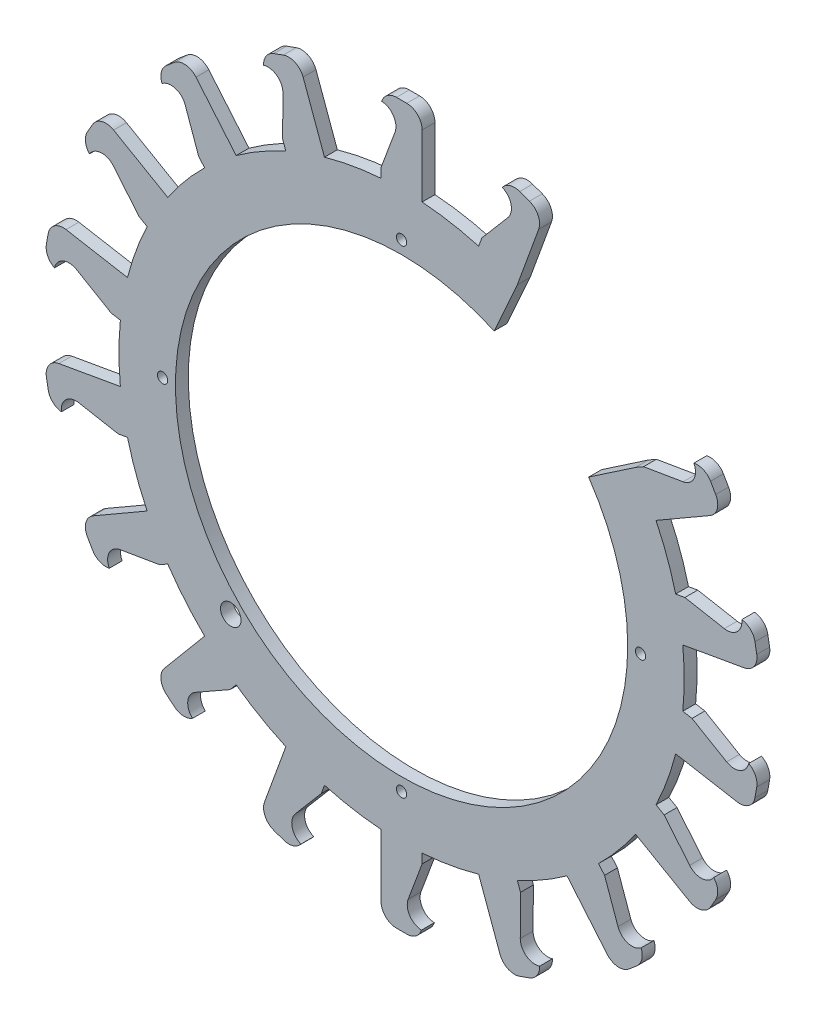
SolidWorks part; units mm, degrees
ref_plane "Front Plane" through (0, 0, 0) normal (0, 0, 1) x (1, 0, 0)
ref_plane "Top Plane" through (0, 0, 0) normal (0, 1, 0) x (1, 0, 0)
ref_plane "Right Plane" through (0, 0, 0) normal (1, 0, 0) x (0, 0, -1)
sketch "Sketch1" plane through (0, 0, 0) normal (0, 0, 1) x (1, 0, 0)
  line L0 (-78.3987, -3.3654) -> (61.3013, -3.3654) construction
  line L1 (-5.8227, 60.5836) -> (-5.8227, 59.1774)
  line L2 (-57.9401, 46.026) -> (40.8427, -52.7569) construction
  line L3 (40.8427, 46.026) -> (-57.9401, -52.7569) construction
  line L4 (-13.4427, 60.5073) -> (-13.4427, 59.1774)
  line L5 (-13.4427, 59.1774) -> (-5.8227, 59.1774)
  line L12 (2.7798, 58.212) -> (10.1401, 56.2398)
  line L13 (10.5041, 57.5981) -> (10.1401, 56.2398)
  line L14 (3.124, 59.4967) -> (2.7798, 58.212)
  line L18 (18.1997, 53.0809) -> (24.7988, 49.2709)
  line L19 (25.5019, 50.4887) -> (24.7988, 49.2709)
  line L20 (18.8647, 54.2327) -> (18.1997, 53.0809)
  line L24 (31.7661, 44.1336) -> (37.1543, 38.7454)
  line L25 (38.1486, 39.7398) -> (37.1543, 38.7454)
  line L26 (32.7065, 45.074) -> (31.7661, 44.1336)
  line L30 (42.5546, 31.9799) -> (46.3646, 25.3808)
  line L31 (47.5824, 26.0839) -> (46.3646, 25.3808)
  line L32 (43.7063, 32.6449) -> (42.5546, 31.9799)
  line L36 (49.8298, 17.4482) -> (51.802, 10.0878)
  line L37 (53.1603, 10.4518) -> (51.802, 10.0878)
  line L38 (51.1145, 17.7924) -> (49.8298, 17.4482)
  line L42 (53.0961, 1.5286) -> (53.0961, -6.0914)
  line L43 (54.5023, -6.0914) -> (53.0961, -6.0914)
  line L44 (54.426, 1.5286) -> (53.0961, 1.5286)
  line L48 (52.1307, -14.6939) -> (50.1585, -22.0543)
  line L49 (51.5168, -22.4183) -> (50.1585, -22.0543)
  line L50 (53.4154, -15.0382) -> (52.1307, -14.6939)
  line L54 (46.9996, -30.1138) -> (43.1896, -36.713)
  line L55 (44.4074, -37.4161) -> (43.1896, -36.713)
  line L56 (48.1513, -30.7788) -> (46.9996, -30.1138)
  line L60 (38.0523, -43.6803) -> (32.6641, -49.0684)
  line L61 (33.6585, -50.0628) -> (32.6641, -49.0684)
  line L62 (38.9927, -44.6207) -> (38.0523, -43.6803)
  line L66 (25.8986, -54.4687) -> (19.2995, -58.2787)
  line L67 (20.0026, -59.4965) -> (19.2995, -58.2787)
  line L68 (26.5636, -55.6205) -> (25.8986, -54.4687)
  line L72 (11.3669, -61.744) -> (4.0065, -63.7162)
  line L73 (4.3705, -65.0745) -> (4.0065, -63.7162)
  line L74 (11.7111, -63.0286) -> (11.3669, -61.744)
  line L78 (-4.5527, -65.0102) -> (-12.1727, -65.0102)
  line L79 (-12.1727, -66.4164) -> (-12.1727, -65.0102)
  line L80 (-4.5527, -66.3402) -> (-4.5527, -65.0102)
  line L84 (-20.7752, -64.0449) -> (-28.1356, -62.0727)
  line L85 (-28.4996, -63.431) -> (-28.1356, -62.0727)
  line L86 (-21.1195, -65.3295) -> (-20.7752, -64.0449)
  line L90 (-36.1951, -58.9137) -> (-42.7943, -55.1037)
  line L91 (-43.4974, -56.3215) -> (-42.7943, -55.1037)
  line L92 (-36.8601, -60.0655) -> (-36.1951, -58.9137)
  line L96 (-49.7616, -49.9665) -> (-55.1497, -44.5783)
  line L97 (-56.1441, -45.5726) -> (-55.1497, -44.5783)
  line L98 (-50.702, -50.9069) -> (-49.7616, -49.9665)
  line L102 (-60.55, -37.8128) -> (-64.36, -31.2137)
  line L103 (-65.5778, -31.9168) -> (-64.36, -31.2137)
  line L104 (-61.7018, -38.4778) -> (-60.55, -37.8128)
  line L109 (-71.1558, -16.2846) -> (-69.7975, -15.9207)
  line L110 (-69.1099, -23.6252) -> (-67.8253, -23.281)
  line L114 (-71.0915, -7.3614) -> (-71.0915, 0.2586)
  line L115 (-72.4977, 0.2586) -> (-71.0915, 0.2586)
  line L116 (-72.4215, -7.3614) -> (-71.0915, -7.3614)
  line L120 (-70.1262, 8.8611) -> (-68.154, 16.2214)
  line L121 (-69.5123, 16.5854) -> (-68.154, 16.2214)
  line L122 (-71.4108, 9.2053) -> (-70.1262, 8.8611)
  line L126 (-64.995, 24.281) -> (-61.185, 30.8801)
  line L127 (-62.4028, 31.5832) -> (-61.185, 30.8801)
  line L128 (-66.1468, 24.946) -> (-64.995, 24.281)
  line L132 (-56.0478, 37.8474) -> (-50.6596, 43.2356)
  line L133 (-51.6539, 44.2299) -> (-50.6596, 43.2356)
  line L134 (-56.9882, 38.7878) -> (-56.0478, 37.8474)
  line L138 (-43.8941, 48.6359) -> (-37.295, 52.4459)
  line L139 (-37.9981, 53.6637) -> (-37.295, 52.4459)
  line L140 (-44.5591, 49.7877) -> (-43.8941, 48.6359)
  line L144 (-29.3623, 55.9111) -> (-22.002, 57.8833)
  line L145 (-22.3659, 59.2416) -> (-22.002, 57.8833)
  line L146 (-29.7065, 57.1958) -> (-29.3623, 55.9111)
  line L147 (-8.9977, -2.9164) -> (-5.8227, 59.1774) construction
  line L148 (-8.9977, -2.9164) -> (10.1401, 56.2398) construction
  line L170 (-67.8253, -23.281) -> (-69.7975, -15.9207) [skipped]
  circle A0 centre (-8.5487, -3.3654) radius 55.88
  circle A1 centre (-8.5487, -3.3654) radius 69.85
  dimension "D1" = 111.76
  dimension "D2" = 139.7
  dimension "D4" = 7.62
  dimension "D5" = 24
  dimension "D6" = 15
extrude "Boss-Extrude1" add sketch "Sketch1" along normal blind 3.175
sketch "Sketch2" plane through (0, 0, 3.175) normal (0, 0, -1) x (-1, 0, 0)
  line L0 (8.5487, 66.4846) -> (8.5487, -73.2154) construction
  line L1 (8.5487, 62.6746) -> (13.6287, 62.6746)
  line L2 (8.5487, 62.6746) -> (3.4687, 62.6746)
  line L3 (3.4687, 62.6746) -> (3.4687, 85.5346)
  line L4 (3.4687, 85.5346) -> (13.6287, 85.5346)
  line L5 (13.6287, 85.5346) -> (13.6287, 62.6746)
  line L6 (8.5487, -3.3654) -> (-61.3013, -3.3654) construction
  line L7 (34.1807, 81.9107) -> (43.7279, 78.4358)
  line L8 (43.7279, 78.4358) -> (35.9094, 56.9544)
  line L9 (26.3621, 60.4293) -> (34.1807, 81.9107)
  line L10 (31.1357, 58.6919) -> (26.3621, 60.4293)
  line L11 (31.1357, 58.6919) -> (35.9094, 56.9544)
  line L12 (61.801, 68.0013) -> (69.584, 61.4705)
  line L13 (69.584, 61.4705) -> (54.8899, 43.9588)
  line L14 (47.1069, 50.4895) -> (61.801, 68.0013)
  line L15 (50.9984, 47.2241) -> (47.1069, 50.4895)
  line L16 (50.9984, 47.2241) -> (54.8899, 43.9588)
  line L17 (82.9984, 45.484) -> (88.0784, 36.6851)
  line L18 (88.0784, 36.6851) -> (68.281, 25.2551)
  line L19 (63.201, 34.054) -> (82.9984, 45.484)
  line L20 (65.741, 29.6546) -> (63.201, 34.054)
  line L21 (65.741, 29.6546) -> (68.281, 25.2551)
  line L22 (95.216, 17.0747) -> (96.9803, 7.0691)
  line L23 (96.9803, 7.0691) -> (74.4676, 3.0995)
  line L24 (72.7033, 13.1051) -> (95.216, 17.0747)
  line L25 (73.5854, 8.1023) -> (72.7033, 13.1051)
  line L26 (73.5854, 8.1023) -> (74.4676, 3.0995)
  line L27 (96.9803, -13.7999) -> (95.216, -23.8056)
  line L28 (95.216, -23.8056) -> (72.7033, -19.836)
  line L29 (74.4676, -9.8303) -> (96.9803, -13.7999)
  line L30 (73.5854, -14.8332) -> (74.4676, -9.8303)
  line L31 (73.5854, -14.8332) -> (72.7033, -19.836)
  line L32 (88.0784, -43.416) -> (82.9984, -52.2149)
  line L33 (82.9984, -52.2149) -> (63.201, -40.7849)
  line L34 (68.281, -31.986) -> (88.0784, -43.416)
  line L35 (65.741, -36.3854) -> (68.281, -31.986)
  line L36 (65.741, -36.3854) -> (63.201, -40.7849)
  line L37 (69.584, -68.2014) -> (61.801, -74.7322)
  line L38 (61.801, -74.7322) -> (47.1069, -57.2204)
  line L39 (54.8899, -50.6897) -> (69.584, -68.2014)
  line L40 (50.9984, -53.955) -> (54.8899, -50.6897)
  line L41 (50.9984, -53.955) -> (47.1069, -57.2204)
  line L42 (43.7279, -85.1667) -> (34.1807, -88.6416)
  line L43 (34.1807, -88.6416) -> (26.3621, -67.1602)
  line L44 (35.9094, -63.6853) -> (43.7279, -85.1667)
  line L45 (31.1357, -65.4227) -> (35.9094, -63.6853)
  line L46 (31.1357, -65.4227) -> (26.3621, -67.1602)
  line L47 (13.6287, -92.2654) -> (3.4687, -92.2654)
  line L48 (3.4687, -92.2654) -> (3.4687, -69.4054)
  line L49 (13.6287, -69.4054) -> (13.6287, -92.2654)
  line L50 (8.5487, -69.4054) -> (13.6287, -69.4054)
  line L51 (8.5487, -69.4054) -> (3.4687, -69.4054)
  line L52 (-17.0832, -88.6416) -> (-26.6305, -85.1667)
  line L53 (-26.6305, -85.1667) -> (-18.8119, -63.6853)
  line L54 (-9.2647, -67.1602) -> (-17.0832, -88.6416)
  line L55 (-14.0383, -65.4227) -> (-9.2647, -67.1602)
  line L56 (-14.0383, -65.4227) -> (-18.8119, -63.6853)
  line L57 (-44.7036, -74.7322) -> (-52.4866, -68.2014)
  line L58 (-52.4866, -68.2014) -> (-37.7925, -50.6897)
  line L59 (-30.0095, -57.2204) -> (-44.7036, -74.7322)
  line L60 (-33.901, -53.955) -> (-30.0095, -57.2204)
  line L61 (-33.901, -53.955) -> (-37.7925, -50.6897)
  line L62 (-65.9009, -52.2149) -> (-70.9809, -43.416)
  line L63 (-70.9809, -43.416) -> (-51.1836, -31.986)
  line L64 (-46.1036, -40.7849) -> (-65.9009, -52.2149)
  line L65 (-48.6436, -36.3854) -> (-46.1036, -40.7849)
  line L66 (-48.6436, -36.3854) -> (-51.1836, -31.986)
  line L67 (-78.1186, -23.8056) -> (-79.8828, -13.7999)
  line L68 (-79.8828, -13.7999) -> (-57.3701, -9.8303)
  line L69 (-55.6059, -19.836) -> (-78.1186, -23.8056)
  line L70 (-56.488, -14.8332) -> (-55.6059, -19.836)
  line L71 (-56.488, -14.8332) -> (-57.3701, -9.8303)
  line L72 (-79.8828, 7.0691) -> (-78.1186, 17.0747)
  line L73 (-78.1186, 17.0747) -> (-55.6059, 13.1051)
  line L74 (-57.3701, 3.0995) -> (-79.8828, 7.0691)
  line L75 (-56.488, 8.1023) -> (-57.3701, 3.0995)
  line L76 (-56.488, 8.1023) -> (-55.6059, 13.1051)
  line L77 (-70.9809, 36.6851) -> (-65.9009, 45.484)
  line L78 (-65.9009, 45.484) -> (-46.1036, 34.054)
  line L79 (-51.1836, 25.2551) -> (-70.9809, 36.6851)
  line L80 (-48.6436, 29.6546) -> (-51.1836, 25.2551)
  line L81 (-48.6436, 29.6546) -> (-46.1036, 34.054)
  line L82 (-52.4866, 61.4705) -> (-44.7036, 68.0013)
  line L83 (-44.7036, 68.0013) -> (-30.0095, 50.4895)
  line L84 (-37.7925, 43.9588) -> (-52.4866, 61.4705)
  line L85 (-33.901, 47.2241) -> (-37.7925, 43.9588)
  line L86 (-33.901, 47.2241) -> (-30.0095, 50.4895)
  line L87 (-26.6305, 78.4358) -> (-17.0832, 81.9107)
  line L88 (-17.0832, 81.9107) -> (-9.2647, 60.4293)
  line L89 (-18.8119, 56.9544) -> (-26.6305, 78.4358)
  line L90 (-14.0383, 58.6919) -> (-18.8119, 56.9544)
  line L91 (-14.0383, 58.6919) -> (-9.2647, 60.4293)
  circle A2 centre (8.5487, -3.3654) radius 69.85 construction
  point P99 (8.5487, -3.3654)
  dimension "D3" = 3.81
  dimension "D1" = 5.08
  dimension "D2" = 5.08
  dimension "D4" = 22.86
  dimension "D5" = 18
extrude "Boss-Extrude2" add sketch "Sketch2" along normal blind 3.175
fillet "Fillet4" radius 3.81 36 edges at (-13.6287, 85.5346, 1.5875) (-3.4687, 85.5346, 1.5875) (-88.0784, 36.6851, 1.5875) (-82.9984, 45.484, 1.5875) (-95.216, 17.0747, 1.5875) (-96.9803, 7.0691, 1.5875) (-96.9803, -13.7999, 1.5875) (-95.216, -23.8056, 1.5875) (-88.0784, -43.416, 1.5875) (-82.9984, -52.2149, 1.5875) (-69.584, -68.2014, 1.5875) (-61.801, -74.7322, 1.5875) (-43.7279, -85.1667, 1.5875) (-34.1807, -88.6416, 1.5875) (-13.6287, -92.2654, 1.5875) (-3.4687, -92.2654, 1.5875) (17.0832, -88.6416, 1.5875) (26.6305, -85.1667, 1.5875) (52.4866, -68.2014, 1.5875) (44.7036, -74.7322, 1.5875) (65.9009, -52.2149, 1.5875) (70.9809, -43.416, 1.5875) (78.1186, -23.8056, 1.5875) (79.8828, -13.7999, 1.5875) (79.8828, 7.0691, 1.5875) (78.1186, 17.0747, 1.5875) (70.9809, 36.6851, 1.5875) (65.9009, 45.484, 1.5875) (52.4866, 61.4705, 1.5875) (44.7036, 68.0013, 1.5875) (26.6305, 78.4358, 1.5875) (17.0832, 81.9107, 1.5875) (-69.584, 61.4705, 1.5875) (-61.801, 68.0013, 1.5875) (-43.7279, 78.4358, 1.5875) (-34.1807, 81.9107, 1.5875)
sketch "Sketch3" plane through (0, 0, 0) normal (0, 0, -1) x (-1, 0, 0)
  line L0 (17.0808, 69.8995) -> (13.6287, 79.1846) construction
  line L1 (13.6287, 66.2996) -> (13.6287, 81.7246) construction
  line L2 (13.6287, 68.616) -> (10.1766, 77.9011)
  line L3 (20.533, 71.183) -> (17.0808, 80.468)
  line L4 (13.6287, 66.2996) -> (13.6287, 81.7246) construction
  line L5 (8.5487, 52.5146) -> (8.5487, -59.2454) construction
  line L6 (-47.3313, -3.3654) -> (64.4287, -3.3654) construction
  line L7 (41.6244, 62.563) -> (41.5561, 72.4687) construction
  line L8 (37.9415, 62.5376) -> (37.8732, 72.4433)
  line L9 (45.3073, 62.5883) -> (45.239, 72.4941)
  line L10 (62.1785, 47.2744) -> (65.5023, 56.6062) construction
  line L11 (58.709, 48.5102) -> (62.0329, 57.8419)
  line L12 (65.648, 46.0387) -> (68.9718, 55.3704)
  line L13 (76.2641, 25.878) -> (82.5791, 33.5101) construction
  line L14 (73.4265, 28.2259) -> (79.7415, 35.858)
  line L15 (79.1017, 23.5301) -> (85.4167, 31.1623)
  line L16 (82.1822, 0.9544) -> (90.7267, 5.9664) construction
  line L17 (80.3188, 4.1312) -> (88.8633, 9.1432)
  line L18 (84.0457, -2.2224) -> (92.5902, 2.7896)
  line L19 (79.219, -24.4903) -> (88.9625, -22.7029) construction
  line L20 (78.5545, -20.8677) -> (88.2979, -19.0804)
  line L21 (79.8836, -28.1128) -> (89.627, -26.3255)
  line L22 (67.732, -47.387) -> (77.4991, -49.0399) construction
  line L23 (68.3465, -43.7556) -> (78.1137, -45.4085)
  line L24 (67.1175, -51.0183) -> (76.8846, -52.6712)
  line L25 (49.1066, -64.974) -> (57.7193, -69.8678) construction
  line L26 (50.926, -61.7718) -> (59.5388, -66.6656)
  line L27 (47.2871, -68.1762) -> (55.8999, -73.07)
  line L28 (25.5892, -75.1302) -> (32.0088, -82.6745) construction
  line L29 (28.3942, -72.7434) -> (34.8138, -80.2878)
  line L30 (22.7843, -77.5169) -> (29.2039, -85.0613)
  line L31 (0.0166, -76.6304) -> (3.4687, -85.9154) construction
  line L32 (3.4687, -75.3469) -> (6.9208, -84.632)
  line L33 (-3.4355, -77.9139) -> (0.0166, -87.1989)
  line L34 (-24.527, -69.2938) -> (-24.4587, -79.1996) construction
  line L35 (-20.844, -69.2685) -> (-20.7758, -79.1742)
  line L36 (-28.2099, -69.3192) -> (-28.1416, -79.225)
  line L37 (-45.0811, -54.0053) -> (-48.4049, -63.3371) construction
  line L38 (-41.6116, -55.2411) -> (-44.9354, -64.5728)
  line L39 (-48.5506, -52.7695) -> (-51.8744, -62.1013)
  line L40 (-59.1667, -32.6089) -> (-65.4817, -40.241) construction
  line L41 (-56.3291, -34.9568) -> (-62.6441, -42.5889)
  line L42 (-62.0043, -30.261) -> (-68.3193, -37.8931)
  line L43 (-65.0848, -7.6853) -> (-73.6293, -12.6973) construction
  line L44 (-63.2213, -10.8621) -> (-71.7659, -15.8741)
  line L45 (-66.9482, -4.5085) -> (-75.4927, -9.5205)
  line L46 (-62.1216, 17.7594) -> (-71.865, 15.972) construction
  line L47 (-61.4571, 14.1368) -> (-71.2005, 12.3495)
  line L48 (-62.7861, 21.3819) -> (-72.5296, 19.5946)
  line L49 (-50.6345, 40.6561) -> (-60.4017, 42.309) construction
  line L50 (-51.2491, 37.0247) -> (-61.0162, 38.6776)
  line L51 (-50.02, 44.2874) -> (-59.7871, 45.9403)
  line L52 (-32.0091, 58.2431) -> (-40.6219, 63.1369) construction
  line L53 (-33.8286, 55.0409) -> (-42.4414, 59.9347)
  line L54 (-30.1896, 61.4453) -> (-38.8024, 66.3391)
  line L55 (-8.4918, 68.3993) -> (-14.9114, 75.9436) construction
  line L56 (-11.2968, 66.0125) -> (-17.7164, 73.5569)
  line L57 (-5.6868, 70.786) -> (-12.1064, 78.3304)
  line L58 (8.5487, -3.3654) -> (17.0808, 69.8995) construction
  arc A0 (13.6287, 68.616) -> (20.533, 71.183) centre (17.0808, 69.8995) ccw
  arc A1 (17.0808, 80.468) -> (10.1766, 77.9011) centre (13.6287, 79.1846) ccw
  circle A2 centre (8.5487, -3.3654) radius 55.88 construction
  arc A3 (37.9415, 62.5376) -> (45.3073, 62.5883) centre (41.6244, 62.563) ccw
  arc A4 (45.239, 72.4941) -> (37.8732, 72.4433) centre (41.5561, 72.4687) ccw
  arc A5 (58.709, 48.5102) -> (65.648, 46.0387) centre (62.1785, 47.2744) ccw
  arc A6 (68.9718, 55.3704) -> (62.0329, 57.8419) centre (65.5023, 56.6062) ccw
  arc A7 (73.4265, 28.2259) -> (79.1017, 23.5301) centre (76.2641, 25.878) ccw
  arc A8 (85.4167, 31.1623) -> (79.7415, 35.858) centre (82.5791, 33.5101) ccw
  arc A9 (80.3188, 4.1312) -> (84.0457, -2.2224) centre (82.1822, 0.9544) ccw
  arc A10 (92.5902, 2.7896) -> (88.8633, 9.1432) centre (90.7267, 5.9664) ccw
  arc A11 (78.5545, -20.8677) -> (79.8836, -28.1128) centre (79.219, -24.4903) ccw
  arc A12 (89.627, -26.3255) -> (88.2979, -19.0804) centre (88.9625, -22.7029) ccw
  arc A13 (68.3465, -43.7556) -> (67.1175, -51.0183) centre (67.732, -47.387) ccw
  arc A14 (76.8846, -52.6712) -> (78.1137, -45.4085) centre (77.4991, -49.0399) ccw
  arc A15 (50.926, -61.7718) -> (47.2871, -68.1762) centre (49.1066, -64.974) ccw
  arc A16 (55.8999, -73.07) -> (59.5388, -66.6656) centre (57.7193, -69.8678) ccw
  arc A17 (28.3942, -72.7434) -> (22.7843, -77.5169) centre (25.5892, -75.1302) ccw
  arc A18 (29.2039, -85.0613) -> (34.8138, -80.2878) centre (32.0088, -82.6745) ccw
  arc A19 (3.4687, -75.3469) -> (-3.4355, -77.9139) centre (0.0166, -76.6304) ccw
  arc A20 (0.0166, -87.1989) -> (6.9208, -84.632) centre (3.4687, -85.9154) ccw
  arc A21 (-20.844, -69.2685) -> (-28.2099, -69.3192) centre (-24.527, -69.2938) ccw
  arc A22 (-28.1416, -79.225) -> (-20.7758, -79.1742) centre (-24.4587, -79.1996) ccw
  arc A23 (-41.6116, -55.2411) -> (-48.5506, -52.7695) centre (-45.0811, -54.0053) ccw
  arc A24 (-51.8744, -62.1013) -> (-44.9354, -64.5728) centre (-48.4049, -63.3371) ccw
  arc A25 (-56.3291, -34.9568) -> (-62.0043, -30.261) centre (-59.1667, -32.6089) ccw
  arc A26 (-68.3193, -37.8931) -> (-62.6441, -42.5889) centre (-65.4817, -40.241) ccw
  arc A27 (-63.2213, -10.8621) -> (-66.9482, -4.5085) centre (-65.0848, -7.6853) ccw
  arc A28 (-75.4927, -9.5205) -> (-71.7659, -15.8741) centre (-73.6293, -12.6973) ccw
  arc A29 (-61.4571, 14.1368) -> (-62.7861, 21.3819) centre (-62.1216, 17.7594) ccw
  arc A30 (-72.5296, 19.5946) -> (-71.2005, 12.3495) centre (-71.865, 15.972) ccw
  arc A31 (-51.2491, 37.0247) -> (-50.02, 44.2874) centre (-50.6345, 40.6561) ccw
  arc A32 (-59.7871, 45.9403) -> (-61.0162, 38.6776) centre (-60.4017, 42.309) ccw
  arc A33 (-33.8286, 55.0409) -> (-30.1896, 61.4453) centre (-32.0091, 58.2431) ccw
  arc A34 (-38.8024, 66.3391) -> (-42.4414, 59.9347) centre (-40.6219, 63.1369) ccw
  arc A35 (-11.2968, 66.0125) -> (-5.6868, 70.786) centre (-8.4918, 68.3993) ccw
  arc A36 (-12.1064, 78.3304) -> (-17.7164, 73.5569) centre (-14.9114, 75.9436) ccw
  point P4 (15.3548, 74.542)
  point P10 (9.1837, -3.8983)
  point P11 (9.1837, -3.8983)
  point P21 (41.5903, 67.5158)
  point P28 (63.8404, 51.9403)
  point P35 (79.4216, 29.6941)
  point P42 (86.4545, 3.4604)
  point P49 (84.0908, -23.5966)
  point P56 (72.6156, -48.2134)
  point P63 (53.4129, -67.4209)
  point P70 (28.799, -78.9023)
  point P77 (1.7427, -81.2729)
  point P84 (-24.4928, -74.2467)
  point P91 (-46.743, -58.6712)
  point P98 (-62.3242, -36.425)
  point P105 (-69.357, -10.1913)
  point P112 (-66.9933, 16.8657)
  point P119 (-55.5181, 41.4825)
  point P126 (-36.3155, 60.69)
  point P131 (9.1837, -3.8983)
  point P133 (9.1837, -3.8983)
  point P134 (9.1837, -3.8983)
  point P135 (9.1837, -3.8983)
  point P136 (9.1837, -3.8983)
  point P137 (9.1837, -3.8983)
  point P138 (9.1837, -3.8983)
  point P139 (9.1837, -3.8983)
  point P140 (9.1837, -3.8983)
  point P141 (9.1837, -3.8983)
  point P142 (9.1837, -3.8983)
  point P143 (9.1837, -3.8983)
  point P144 (9.1837, -3.8983)
  point P145 (9.1837, -3.8983)
  point P146 (9.1837, -3.8983)
  point P152 (-11.7016, 72.1715)
  dimension "D1" = 7.366
  dimension "D2" = 6.35
  dimension "D3" = 9.906
  dimension "D4" = 18
  dimension "D5" = 73.7601
extrude "Cut-Extrude1" cut sketch "Sketch3" against normal through all
sketch "Sketch4" plane through (0, 0, 0) normal (0, 0, -1) x (-1, 0, 0)
  line L0 (8.5487, 52.5146) -> (8.5487, -59.2454) construction
  line L1 (-47.3313, -3.3654) -> (64.4287, -3.3654) construction
  line L2 (8.5487, -3.3654) -> (81.6471, -76.4638) construction
  line L3 (8.5487, -3.3654) -> (-56.7065, 61.8898) construction
  line L4 (-49.243, 35.8665) -> (-37.6846, 28.0201)
  line L5 (-20.0518, 60.3608) -> (-14.3317, 47.6156)
  line L6 (-49.243, 35.8665) -> (-56.7065, 61.8898)
  line L7 (-56.7065, 61.8898) -> (-31.4348, 76.896)
  line L8 (-31.4348, 76.896) -> (-20.0518, 60.3608)
  line L9 (-14.3317, 47.6156) -> (-37.6846, 28.0201)
  circle A0 centre (8.5487, -3.3654) radius 55.88 construction
  circle A1 centre (8.5487, -3.3654) radius 59.055
  circle A2 centre (8.5487, 55.6896) radius 1.27
  circle A3 centre (8.5487, -62.4204) radius 1.27
  circle A4 centre (-50.5063, -3.3654) radius 1.27
  circle A5 centre (67.6037, -3.3654) radius 1.27
  circle A6 centre (8.5487, -3.3654) radius 62.23
  circle A8 centre (50.7559, -45.5726) radius 2.54
  dimension "D1" = 118.11
  dimension "D2" = 2.54
  dimension "D3" = 2.54
  dimension "D4" = 2.54
  dimension "D5" = 2.54
  dimension "D8" = 124.46
  dimension "D10" = 5.08
  dimension "D6" = 45
  dimension "D7" = 45
extrude "Cut-Extrude2" cut sketch "Sketch4" against normal through all contours A6 L5 L8 L7 L6 L4 | L5 A6 L4 A1 | L5 A1 L4 L9 | A1 A2 | A1 A2 | A1 A5 | A1 A5 | A1 A8 | A1 A8 | A1 A3 | A1 A3 | A1 A4 | A1 A4
